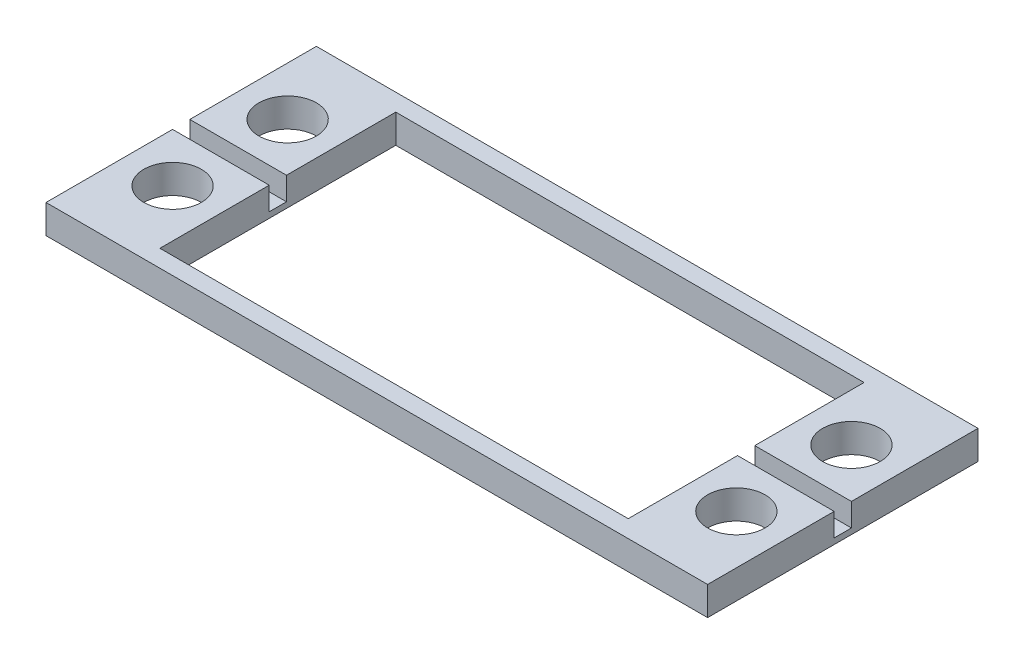
SolidWorks part; units mm, degrees
ref_plane "Front Plane" through (0, 0, 0) normal (0, 0, 1) x (1, 0, 0)
ref_plane "Top Plane" through (0, 0, 0) normal (0, 1, 0) x (1, 0, 0)
ref_plane "Right Plane" through (0, 0, 0) normal (1, 0, 0) x (0, 0, -1)
sketch "Sketch2" plane through (0, 0, 0) normal (0, 1, 0) x (1, 0, 0)
  line L0 (-47.9291, 36.8099) -> (-23.4291, 36.8099) construction
  line L5 (-68.2791, 47.0599) -> (-27.5791, 47.0599)
  line L6 (-68.2791, 47.0599) -> (-68.2791, 26.5599)
  line L7 (-68.2791, 26.5599) -> (-27.5791, 26.5599)
  line L8 (-27.5791, 47.0599) -> (-27.5791, 26.5599)
  line L9 (-68.2791, 47.0599) -> (-27.5791, 26.5599) construction
  line L10 (-68.2791, 26.5599) -> (-27.5791, 47.0599) construction
  line L11 (-23.4291, 36.8099) -> (-23.4291, 41.8099) construction
  line L12 (-47.9291, 47.0599) -> (-47.9291, 26.5599) construction
  line L14 (-76.6791, 25.0599) -> (-19.1791, 25.0599)
  line L15 (-76.6791, 25.0599) -> (-76.6791, 48.5599)
  line L16 (-76.6791, 48.5599) -> (-19.1791, 48.5599)
  line L17 (-19.1791, 25.0599) -> (-19.1791, 48.5599)
  line L18 (-76.6791, 25.0599) -> (-19.1791, 48.5599) construction
  line L19 (-76.6791, 48.5599) -> (-19.1791, 25.0599) construction
  circle A0 centre (-23.4291, 41.8099) radius 2.5
  circle A1 centre (-23.4291, 31.8099) radius 2.5
  circle A2 centre (-72.4291, 31.8099) radius 2.5
  circle A3 centre (-72.4291, 41.8099) radius 2.5
  point P0 (-47.9291, 36.8099)
  dimension "D5" = 5
  dimension "D6" = 57.5
  dimension "D1" = 20.5
  dimension "D2" = 40.7
  dimension "D3" = 24.5
  dimension "D4" = 5
  dimension "D7" = 23.5
extrude "Boss-Extrude1" add sketch "Sketch2" along normal blind 2.5
sketch "Sketch3" plane through (0, 2.5, 0) normal (0, 1, 0) x (1, 0, 0)
  line L0 (-76.6791, 36.8099) -> (-19.1791, 36.8099) construction
  line L1 (-76.6791, 48.5599) -> (-76.6791, 25.0599) construction
  line L2 (-19.1791, 25.0599) -> (-19.1791, 48.5599) construction
  line L5 (-27.5791, 36.8099) -> (-27.5791, 36.0599)
  line L6 (-27.5791, 26.5599) -> (-27.5791, 47.0599) construction
  line L7 (-27.5791, 36.8099) -> (-27.5791, 37.5599)
  line L8 (-27.5791, 36.0599) -> (-19.1791, 36.0599)
  line L9 (-19.1791, 36.0599) -> (-19.1791, 37.5599)
  line L10 (-19.1791, 37.5599) -> (-27.5791, 37.5599)
  line L11 (-47.9291, 48.5599) -> (-47.9291, 25.0599) construction
  line L12 (-19.1791, 48.5599) -> (-76.6791, 48.5599) construction
  line L13 (-76.6791, 25.0599) -> (-19.1791, 25.0599) construction
  line L14 (-76.6791, 37.5599) -> (-68.2791, 37.5599)
  line L15 (-76.6791, 36.0599) -> (-76.6791, 37.5599)
  line L16 (-68.2791, 36.0599) -> (-76.6791, 36.0599)
  line L17 (-68.2791, 36.8099) -> (-68.2791, 37.5599)
  line L18 (-68.2791, 36.8099) -> (-68.2791, 36.0599)
  point P9 (-27.5791, 46.3099)
  point P15 (-27.5791, 39.1175)
  point P29 (-68.2791, 39.1175)
  dimension "D1" = 0.75
extrude "Cut-Extrude1" cut sketch "Sketch3" against normal blind 2
